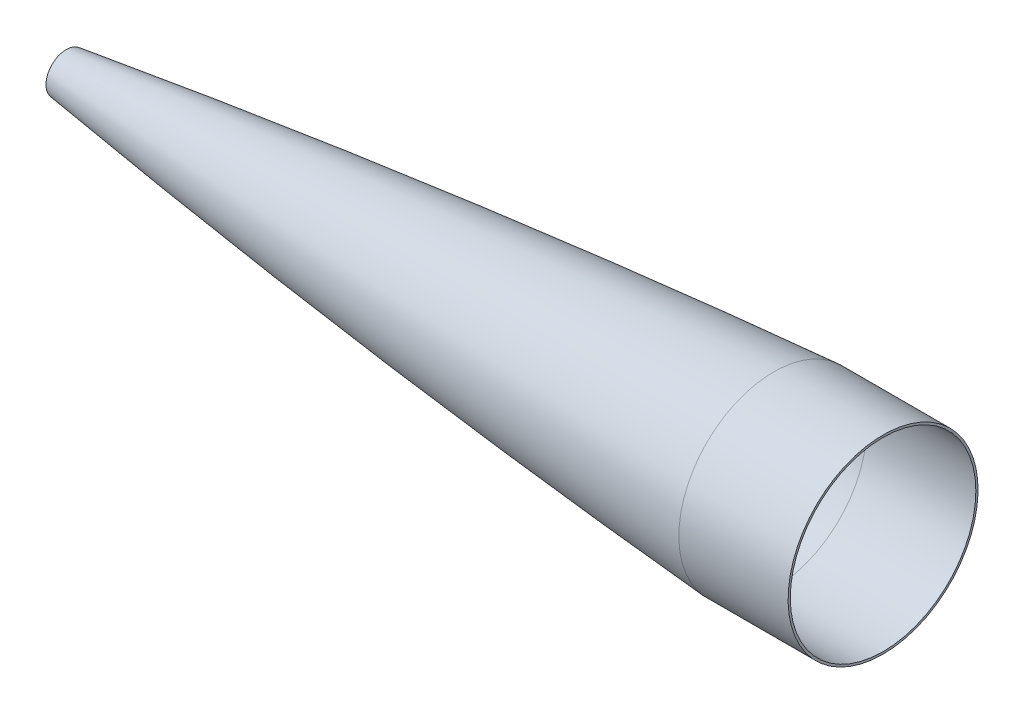
SolidWorks part; units mm, degrees
other "Markup1"
sketch "Sketch19" plane through (863.2353, 87, -87) normal (0.5122, 0.1711, -0.8417) x (-0.8532, -0.0108, -0.5214)
other "Markup2"
sketch "Sketch20" plane through (863.2353, 87, -87) normal (0.5122, 0.1711, -0.8417) x (-0.8532, -0.0108, -0.5214)
material "E-Glass Fiber"
ref_plane "Płaszczyzna przednia" through (0, 0, 0) normal (0, 0, 1) x (1, 0, 0)
ref_plane "Płaszczyzna górna" through (0, 0, 0) normal (0, 1, 0) x (1, 0, 0)
ref_plane "Płaszczyzna prawa" through (0, 0, 0) normal (1, 0, 0) x (0, 0, -1)
ref_plane "Plane1" through (0, 0, 0) normal (0, 0, -1) x (-1, 0, 0)
sketch "Sketch1" plane through (0, 0, 0) normal (0, 0, -1) x (-1, 0, 0)
  line L2 (-763.2353, 0) -> (0, 0) construction
  line L8 (-763.3824, 85) -> (-763.2353, 85)
  line L9 (-763.3824, 87) -> (-763.1616, 87)
  line L10 (0, 0) -> (18.4685, 0)
  line L11 (18.4685, 0) -> (0.2953, 1.9781)
  line L12 (-763.3824, 87) -> (-763.3824, 85)
  line L13 (18.4685, 0) -> (-161.5315, 0)
  line L14 (-161.5315, 0) -> (-161.5315, 22.8102)
  arc A0 (-161.5315, 22.8102) -> (-763.2353, 85) centre (-1520.6726, -10185.346) ccw
  arc A3 (0.2953, 1.9781) -> (-763.1616, 87) centre (-1520.6726, -10185.346) ccw
  arc A4 (0, 0) -> (-763.2353, 85) centre (-1520.6726, -10185.346) ccw construction
  dimension "D1" = 85
  dimension "D2" = 2
revolve "Revolve1" add sketch "Sketch1" angle 360 about L2
sketch "Sketch14" plane through (0, 0, 0) normal (0, 0, -1) x (-1, 0, 0)
  line L0 (-763.2353, 85) -> (-763.2353, -85) construction
  line L1 (-763.2353, 0) -> (-863.2353, 0) construction
  line L2 (-863.2353, 0) -> (-863.2353, 85) construction
  line L9 (-763.3824, 87) -> (-763.3824, 85)
  line L10 (-763.3824, 87) -> (-863.2353, 87)
  line L11 (-863.2353, 87) -> (-863.2353, 85)
  line L12 (-763.3824, 85) -> (-863.2353, 85)
  arc A0 (-763.2353, -85) -> (-161.5315, -22.8102) centre (-1520.6726, 10185.346) ccw construction
  dimension "D1" = 100
revolve "Revolve4" add sketch "Sketch14" angle 360 about L1
sketch "Sketch15" plane through (0, 0, 0) normal (0, 0, 1) x (1, 0, 0)
  line L0 (-17.7797, -0.075) -> (114.9971, 0)
  line L1 (-18.4685, 0) -> (-0.2953, -1.9781) construction
  line L2 (763.2353, 0) -> (0, 0) construction
  line L3 (114.9971, 0) -> (114.9971, 42.3088)
  line L4 (114.9971, 42.3088) -> (-24.7937, 42.3088)
  line L5 (-24.7937, 42.3088) -> (-24.7937, -36.0986)
  line L6 (-24.7937, -36.0986) -> (114.9971, -36.0986)
  line L7 (114.9971, -36.0986) -> (114.9971, 0)
  line L8 (114.9971, 0) -> (114.9971, -36.0986)
  dimension "D1" = 132.7768
extrude "Cut-Extrude1" cut sketch "Sketch15" along normal mid plane 100
sketch "Sketch21" plane through (114.9971, 0, 0) normal (-1, 0, 0) x (0, 0, 1)
  circle A0 centre (0, 0) radius 3
extrude "Cut-Extrude2" cut sketch "Sketch21" against normal up to next
